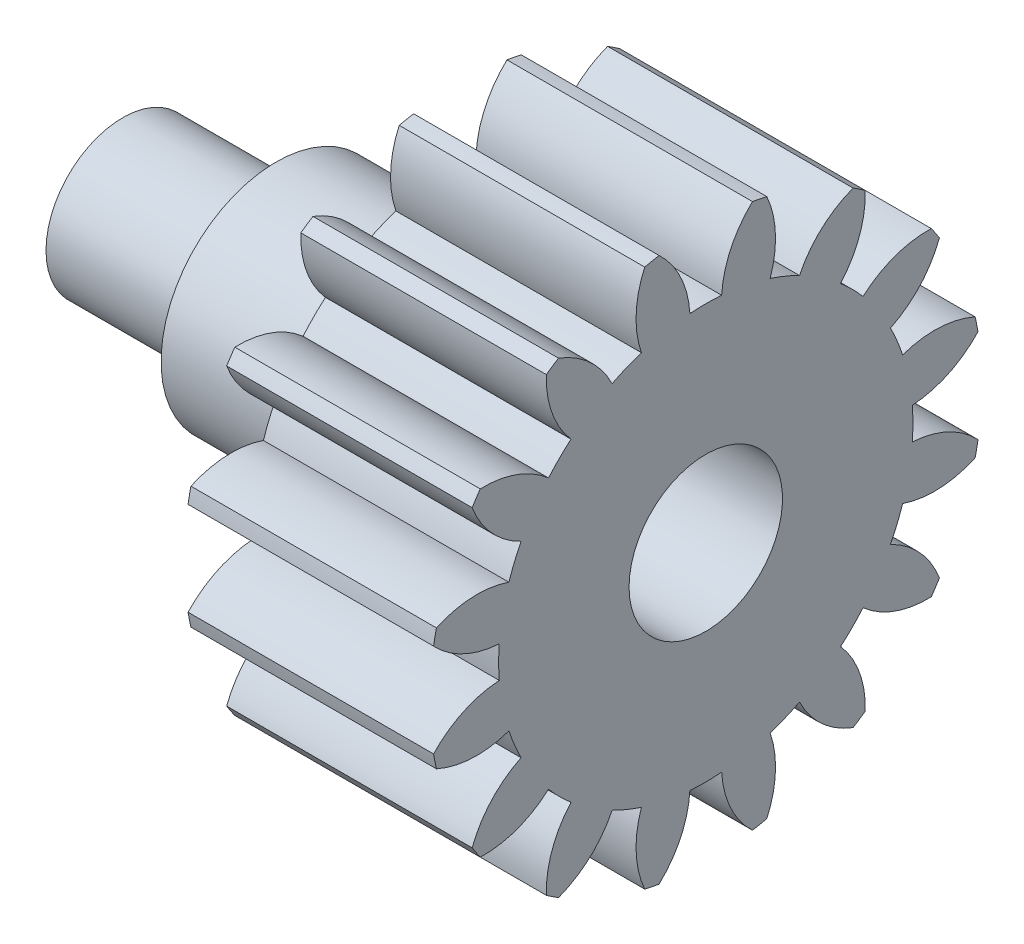
SolidWorks part; units mm, degrees
ref_plane "Plane1" through (0, 0, 0) normal (0, 0, 1) x (1, 0, 0)
ref_plane "Plane2" through (0, 0, 0) normal (0, 1, 0) x (1, 0, 0)
ref_plane "Plane3" through (0, 0, 0) normal (1, 0, 0) x (0, 0, -1)
other "Configuration Table"
sketch "HoldingSke" plane through (0, 0, 0) normal (0, 1, 0) x (1, 0, 0)
  line L0 (0, 0) -> (0.4806, -0.1378)
  line L1 (-15, 0) -> (100, 0) construction
  line L2 (0, 0) -> (-2.1039, 2.3779)
  line L3 (0, 0) -> (-11.863, 4.5341)
  line L4 (0, 0) -> (8.3015, 2.3804)
  line L5 (0, 0) -> (-35.6042, -13.2793)
  line L6 (0, 0) -> (-13.2634, -8.9489)
  line L7 (-2.1039, 2.3779) -> (6.0756, 39.4872)
  line L8 (-76.2, 54.61) -> (-74.4, 54.61)
  line L9 (-71.009, 38.7566) -> (-53.1078, 45.2721)
  line L10 (-76.2, 71.12) -> (104.1128, 71.12)
  line L11 (0, 0) -> (-16, 0)
  line L12 (-76.2, 101.6) -> (-76.133, 101.6)
  line L13 (24.9733, 27.94) -> (52.9518, 28.4284)
  line L14 (24.9733, 27.94) -> (24.9743, 27.94)
  line L15 (24.9733, 27.94) -> (100.4006, 29.5858)
  line L16 (-63.627, -2) -> (-12.827, -2)
  circle A0 centre (0, 0) radius 5
  circle A1 centre (0, 0) radius 7.5
  circle A2 centre (0, 0) radius 7.5
  circle A3 centre (0, 0) radius 5
  dimension "MHD" = 15
  dimension "Hub_dia" = 15
  dimension "Bore" = 10
  dimension "MBD" = 10
  dimension "Num_teeth" = 16
  dimension "Pitch" = 0.5
  dimension "Overall_len" = 38
  dimension "Show_teeth" = 16
  dimension "Thickness" = 16
  dimension "OAL" = 38.0001
  dimension "T_dim" = 1.8
  dimension "Ap" = 20
  dimension "H" = 19.05
  dimension "Pitch_radius" = 180.3128
  dimension "Width" = 16
  dimension "Backlash" = 0.067
  dimension "Addendum_fac" = 1
  dimension "Dedendum_fac" = 1.25
  dimension "Clearance_fac" = 0.25
  dimension "Dedendum_add" = 0.001
  dimension "Module" = 2
sketch "BasProSke" plane through (0, 0, 0) normal (0, 1, 0) x (1, 0, 0)
  line L0 (-10, 0) -> (60, 0) construction
  line L1 (0, 0) -> (0, 18)
  line L2 (0, 0) -> (16, 0)
  line L3 (16, 0) -> (16, 18)
  line L4 (16, 18) -> (0, 18)
  dimension "Thickness" = 16
  dimension "Diameter" = 36
revolve "Base-Revolve" add sketch "BasProSke" angle 360 about L0
sketch "TooCutSke" plane through (0, 0, 0) normal (1, 0, 0) x (0, 0, -1)
  line L1 (0, 0) -> (0, 107) construction
  line L2 (0, 0) -> (-1.6854, 15.911) construction
  line L3 (0, 0) -> (-6.2172, 31.2558) construction
  line L4 (-1.6854, 15.911) -> (-3.1086, 15.6279) construction
  arc A0 (1.0343, 13.4593) -> (-1.0343, 13.4593) centre (0, 0) ccw
  arc A1 (3.0657, 17.7628) -> (-3.0657, 17.7628) centre (0, 0) ccw
  circle A2 centre (0, 0) radius 16 construction
  circle A3 centre (0, 0) radius 15.0351 construction
  arc A4 (-1.0343, 13.4593) -> (-3.0657, 17.7628) centre (-7.4228, 13.075) ccw
  arc A5 (3.0657, 17.7628) -> (1.0343, 13.4593) centre (7.4228, 13.075) ccw
  dimension "Root_dia" = 26.998
  dimension "Overcut_dia" = 36.0508
  dimension "Pitch_dia" = 32
  dimension "Base_dia" = 30.0702
  dimension "Flank_rad" = 6.4
  dimension "Half_ang" = 11.25
  dimension "Half_CT" = 1.451
extrude "ToothCut" cut sketch "TooCutSke" along normal through all
fillet "Breaks" [suppressed] radius 0.04
fillet "RootFillets" [suppressed] radius 0.501
pattern_circular "TeethCuts" count 16 every 22.5 about axis through (-10, 0, 0) along (1, 0, 0) of "ToothCut", "RootFillets", "Breaks"
sketch "HubNeaOneSke" plane through (0, 0, 0) normal (-1, 0, 0) x (0, 0, 1)
  circle A0 centre (0, 0) radius 7.5
  dimension "Diameter" = 15
extrude "HubNearOne" add sketch "HubNeaOneSke" along normal blind 22.0001
sketch "HubNeaBotSke" plane through (0, 0, 0) normal (-1, 0, 0) x (0, 0, 1)
  circle A0 centre (0, 0) radius 7.5
  dimension "Diameter" = 15
extrude "HubNearBoth" [suppressed] add sketch "HubNeaBotSke" along normal blind 11
ref_plane "FarPln" through (16, 0, 0) normal (1, 0, 0) x (0, 0, -1)
sketch "HubFarSke" plane through (16, 0, 0) normal (1, 0, 0) x (0, 0, -1)
  circle A0 centre (0, 0) radius 7.5
  dimension "Diameter" = 15
extrude "HubFar" [suppressed] add sketch "HubFarSke" along normal blind 11
sketch "BorSke" plane through (0, 0, 0) normal (1, 0, 0) x (0, 0, -1)
  circle A0 centre (0, 0) radius 5
  dimension "Diameter" = 10
extrude "Bore" cut sketch "BorSke" along normal mid plane 76.0001
sketch "KeySke" plane through (0, 0, 0) normal (1, 0, 0) x (0, 0, -1)
  line L0 (-2, 0) -> (-2, 6.8)
  line L1 (-2, 6.8) -> (2, 6.8)
  line L2 (2, 6.8) -> (2, 0)
  line L3 (0, 0) -> (0, 34) construction
  line L4 (-2, 0) -> (2, 0)
  dimension "Offset" = 6.8
  dimension "Width" = 4
extrude "Keyway" [suppressed] cut sketch "KeySke" along normal mid plane 76.0001
pattern_circular "Keyway2" [suppressed] count 2 every 90 about axis through (-10, 0, 0) along (1, 0, 0)
sketch "Sketch1" [suppressed] plane through (-15, 0, 0) normal (-1, 0, 0) x (0, 0, 1)
  circle A1 centre (0, 0) radius 5
  circle A2 centre (0, 0) radius 5
  dimension "D1" = 0
sketch "Sketch2" [suppressed] plane through (-15, 0, 0) normal (-1, 0, 0) x (0, 0, 1)
  circle A1 centre (0, 0) radius 5
  circle A2 centre (0, 0) radius 5
  dimension "D1" = 0
sketch "Sketch3" plane through (-22.0001, 0, 0) normal (-1, 0, 0) x (0, 0, 1)
  circle A1 centre (0, 0) radius 7.5
  circle A2 centre (0, 0) radius 7.5
  dimension "D1" = 0
extrude "Cut-Extrude1" cut sketch "Sketch3" against normal blind 10
sketch "Sketch4" plane through (-12.0001, 0, 0) normal (-1, 0, 0) x (0, 0, 1)
  circle A1 centre (0, 0) radius 7.5
  circle A2 centre (0, 0) radius 7.5
  dimension "D1" = 0
extrude "Boss-Extrude1" add sketch "Sketch4" against normal blind 10
sketch "Sketch5" plane through (-12.0001, 0, 0) normal (-1, 0, 0) x (0, 0, 1)
  circle A0 centre (0, 0) radius 5
  dimension "D1" = 10
extrude "Boss-Extrude2" add sketch "Sketch5" along normal blind 10
equation "' \"Module@HoldingSke\" = 6.35"
equation "' \"Num_teeth@HoldingSke\" = 12"
equation "' \"Ap@HoldingSke\" =  20"
equation "' \"Ap@HoldingSke\" = 20"
equation "' \"Width@HoldingSke\" = 0.5 * 25.4"
equation "' \"Hub_dia@HoldingSke\"= 1 * 25.4"
equation "' \"Hub_dia@HoldingSke\" = 1 * 25.4"
equation "' \"Overall_len@HoldingSke\" = 1.0 * 25.4"
equation "' \"Bore@HoldingSke\" = 0.75 * 25.4"
equation "' \"T_dim@HoldingSke\" = 0.1 * 25.4"
equation "' \"Width@KeySke\" = 0.25 * 25.4"
equation "' \"Show_teeth@HoldingSke\" = 13"
equation "' \"Backlash@HoldingSke\" = 0.009 * 25.4"
equation "' \"Addendum_fac@HoldingSke\" = 1.0"
equation "' \"Dedendum_fac@HoldingSke\" = 1.25"
equation "' \"Dedendum_add@HoldingSke\" = 0.00005 * 25.4"
equation "' \"Clearance_fac@HoldingSke\" = 0.25"
equation "\"Pitch@HoldingSke\" = 1 / \"Module@HoldingSke\""
equation "\"Overcut_dia@TooCutSke\" = (\"Num_teeth@HoldingSke\" + 2 * \"Addendum_fac@HoldingSke\") / \"Pitch@HoldingSke\" + 0.002 * 25.4"
equation "\"Pitch_dia@TooCutSke\" = \"Num_teeth@HoldingSke\" / \"Pitch@HoldingSke\""
equation "\"Base_dia@TooCutSke\" = \"Num_teeth@HoldingSke\" / \"Pitch@HoldingSke\" * cos((\"Ap@HoldingSke\"  * 3.14159265 / 180))"
equation "\"Root_dia@TooCutSke\" = (\"Num_teeth@HoldingSke\" + 2) / \"Pitch@HoldingSke\" - 2 * (\"Addendum_fac@HoldingSke\" + \"Dedendum_fac@HoldingSke\") / \"Pitch@HoldingSke\" - \"Dedendum_add@HoldingSke\" * 2"
equation "\"Half_ang@TooCutSke\" = 180 / \"Num_teeth@HoldingSke\""
equation "\"Half_CT@TooCutSke\" = \"Num_teeth@HoldingSke\" / \"Pitch@HoldingSke\" * sin((3.14159265 / 2 / \"Num_teeth@HoldingSke\")) / 2 - 7 * \"Backlash@HoldingSke\" / 4"
equation "\"Flank_rad@TooCutSke\" = \"Num_teeth@HoldingSke\" / \"Pitch@HoldingSke\" / 5"
equation "\"Radius@RootFillets\" = \"Clearance_fac@HoldingSke\" / \"Pitch@HoldingSke\" + \"Dedendum_add@HoldingSke\""
equation "\"Break_rad@Breaks\" = 0.02 / \"Pitch@HoldingSke\""
equation "\"Thickness@HoldingSke\" = \"Width@HoldingSke\""
equation "\"OAL@HoldingSke\" = \"Thickness@HoldingSke\""
equation "\"MHD@HoldingSke\" = (\"Num_teeth@HoldingSke\" + 2) / \"Pitch@HoldingSke\" - 2 * (\"Addendum_fac@HoldingSke\" + \"Dedendum_fac@HoldingSke\")  / \"Pitch@HoldingSke\" - \"Dedendum_add@HoldingSke\" * 2"
equation "\"MBD@HoldingSke\" = (\"Num_teeth@HoldingSke\" + 2) / \"Pitch@HoldingSke\" - 2 * (\"Addendum_fac@HoldingSke\" + \"Dedendum_fac@HoldingSke\")  / \"Pitch@HoldingSke\" - \"Dedendum_add@HoldingSke\" * 2 - 0.002 * 25.4"
equation "\"MHD@HoldingSke\" = ((sgn( \"MHD@HoldingSke\" - \"Hub_dia@HoldingSke\" )-1)*( \"MHD@HoldingSke\" - \"Hub_dia@HoldingSke\" ))/-2+ \"Hub_dia@HoldingSke\""
equation "\"MBD@HoldingSke\" = ((sgn( \"MBD@HoldingSke\" - \"Bore@HoldingSke\" )-1)*( \"MBD@HoldingSke\" - \"Bore@HoldingSke\" ))/-2+ \"Bore@HoldingSke\""
equation "\"OAL@HoldingSke\" = ((sgn( \"OAL@HoldingSke\" - \"Overall_len@HoldingSke\" )+1)*( \"OAL@HoldingSke\" - \"Overall_len@HoldingSke\" ))/2 + \"Overall_len@HoldingSke\" + 0.000002 * 25.4"
equation "\"Num_teeth@TeethCuts\" = int( \"Show_teeth@HoldingSke\" ) + 1"
equation "\"Num_teeth@TeethCuts\" = ((sgn( \"Num_teeth@TeethCuts\" - \"Num_teeth@HoldingSke\" )-1)*( \"Num_teeth@TeethCuts\" - \"Num_teeth@HoldingSke\" ))/-2+ \"Num_teeth@HoldingSke\""
equation "\"Num_teeth@TeethCuts\" = ((sgn( \"Num_teeth@TeethCuts\" - 2.0)+1)*( \"Num_teeth@TeethCuts\" - 2.0))/2 +2.0"
equation "\"Angle@TeethCuts\" = 360.0 / \"Num_teeth@HoldingSke\""
equation "\"Diameter@BasProSke\" = (\"Num_teeth@HoldingSke\" + 2 * \"Addendum_fac@HoldingSke\") / \"Pitch@HoldingSke\""
equation "\"Thickness@BasProSke\"  = \"Thickness@HoldingSke\""
equation "' \"Fillet_rad@BasProSke\" =  \"Thickness@HoldingSke\" * 0.05"
equation "' \"Fillet_rad@BasProSke\" = \"Thickness@HoldingSke\" * 0.05"
equation "\"MHD@HoldingSke\" = ((sgn( \"MHD@HoldingSke\" - \"Root_dia@TooCutSke\" )-1)*( \"MHD@HoldingSke\" - \"Root_dia@TooCutSke\" ))/-2+ \"Root_dia@TooCutSke\""
equation "\"Diameter@HubNeaOneSke\" = \"MHD@HoldingSke\""
equation "\"Length@HubNearOne\" = \"OAL@HoldingSke\" - \"Thickness@BasProSke\""
equation "\"Diameter@HubNeaBotSke\" = \"MHD@HoldingSke\""
equation "\"Length@HubNearBoth\" = ( \"OAL@HoldingSke\" - \"Thickness@BasProSke\" ) / 2.0"
equation "\"Thickness@FarPln\" = \"Thickness@BasProSke\""
equation "\"Diameter@HubFarSke\" = \"MHD@HoldingSke\""
equation "\"Length@HubFar\" = ( \"OAL@HoldingSke\" - \"Thickness@BasProSke\" ) / 2.0"
equation "\"Diameter@BorSke\" = \"MBD@HoldingSke\""
equation "\"D1@Bore\" = \"OAL@HoldingSke\" * 2.0"
equation "\"D1@Keyway\" = \"OAL@HoldingSke\" * 2.0"
equation "\"Offset@KeySke\" = \"T_dim@HoldingSke\" + \"MBD@HoldingSke\" / 2.0"
